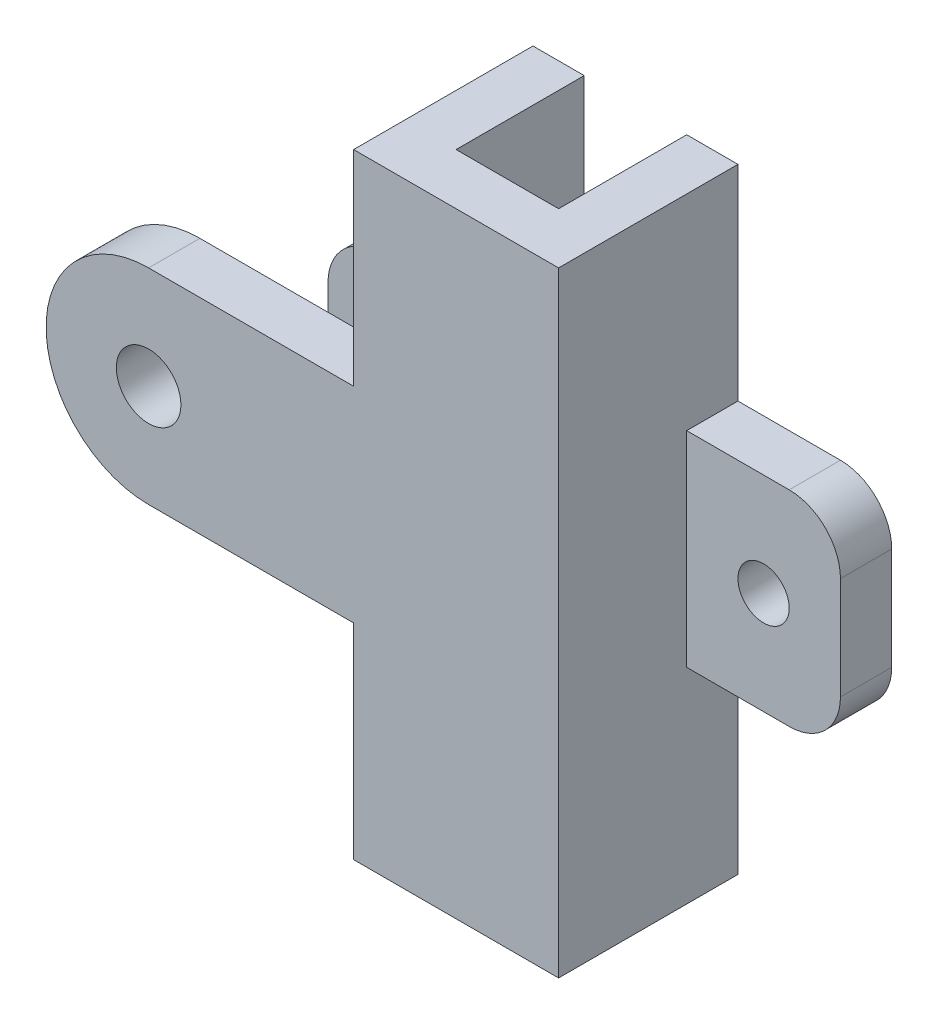
SolidWorks part; units mm, degrees
ref_plane "Front Plane" through (0, 0, 0) normal (0, 0, 1) x (1, 0, 0)
ref_plane "Top Plane" through (0, 0, 0) normal (0, 1, 0) x (1, 0, 0)
ref_plane "Right Plane" through (0, 0, 0) normal (1, 0, 0) x (0, 0, -1)
sketch "Sketch2" plane through (0, 0, 0) normal (0, 1, 0) x (1, 0, 0)
  line L1 (0, 0) -> (25.4, 0)
  line L2 (0, 0) -> (0, 22.225)
  line L3 (0, 22.225) -> (25.4, 22.225)
  line L4 (25.4, 0) -> (25.4, 22.225)
  line L5 (6.35, 22.225) -> (19.05, 22.225)
  line L6 (6.35, 22.225) -> (6.35, 6.35)
  line L7 (6.35, 6.35) -> (19.05, 6.35)
  line L8 (19.05, 22.225) -> (19.05, 6.35)
  dimension "D1" = 25.4
  dimension "D2" = 22.225
  dimension "D3" = 6.35
  dimension "D4" = 6.35
  dimension "D5" = 6.35
extrude "Boss-Extrude1" add sketch "Sketch2" along normal blind 76.2 contours L3 L8 L7 L6 L2 L1 L4
sketch "Sketch3" plane through (0, 0, 0) normal (0, 0, 1) x (1, 0, 0)
  line L1 (25.4, 76.2) -> (0, 76.2) construction
  line L2 (0, 76.2) -> (0, 0) construction
  line L3 (0, 0) -> (25.4, 0) construction
  line L4 (12.7, 50.8) -> (-25.4, 50.8)
  line L6 (-25.4, 25.4) -> (12.7, 25.4)
  arc A1 (12.7, 50.8) -> (12.7, 25.4) centre (12.7, 38.1) cw
  arc A2 (-25.4, 50.8) -> (-25.4, 25.4) centre (-25.4, 38.1) ccw
  circle A3 centre (-25.4, 38.1) radius 4.0005
  point P11 (12.7, 76.2)
  point P12 (12.7, 0)
  point P13 (0, 38.1)
  dimension "D1" = 12.7
  dimension "D3" = 8.001
  dimension "D2" = 38.1
extrude "Boss-Extrude2" add sketch "Sketch3" against normal blind 6.35
sketch "Sketch4" plane through (0, 0, -22.225) normal (0, 0, -1) x (-1, 0, 0)
  line L0 (-25.4, 76.2) -> (-25.4, 0) construction
  line L1 (-25.4, 50.8) -> (-44.45, 50.8)
  line L2 (-25.4, 50.8) -> (-25.4, 25.4)
  line L3 (-25.4, 25.4) -> (-44.45, 25.4)
  line L4 (-44.45, 50.8) -> (-44.45, 25.4)
  line L5 (-44.45, 38.1) -> (-25.4, 38.1) construction
  line L6 (-34.925, 50.8) -> (-34.925, 25.4) construction
  line L7 (-25.4, 76.2) -> (0, 76.2) construction
  line L8 (-25.4, 0) -> (0, 0) construction
  line L9 (-12.7, 76.2) -> (-12.7, 0) construction
  line L10 (0, 25.4) -> (19.05, 25.4)
  line L11 (19.05, 50.8) -> (19.05, 25.4)
  line L12 (0, 50.8) -> (19.05, 50.8)
  line L13 (0, 50.8) -> (0, 25.4)
  circle A0 centre (-34.925, 38.1) radius 3.175
  circle A1 centre (9.525, 38.1) radius 3.175
  dimension "D4" = 6.35
  dimension "D1" = 25.4
  dimension "D2" = 25.4
  dimension "D3" = 19.05
extrude "Boss-Extrude3" add sketch "Sketch4" against normal blind 6.35
fillet "Fillet1" radius 6.35 4 edges at (44.45, 25.4, -19.05) (44.45, 50.8, -19.05) (-19.05, 25.4, -19.05) (-19.05, 50.8, -19.05)
